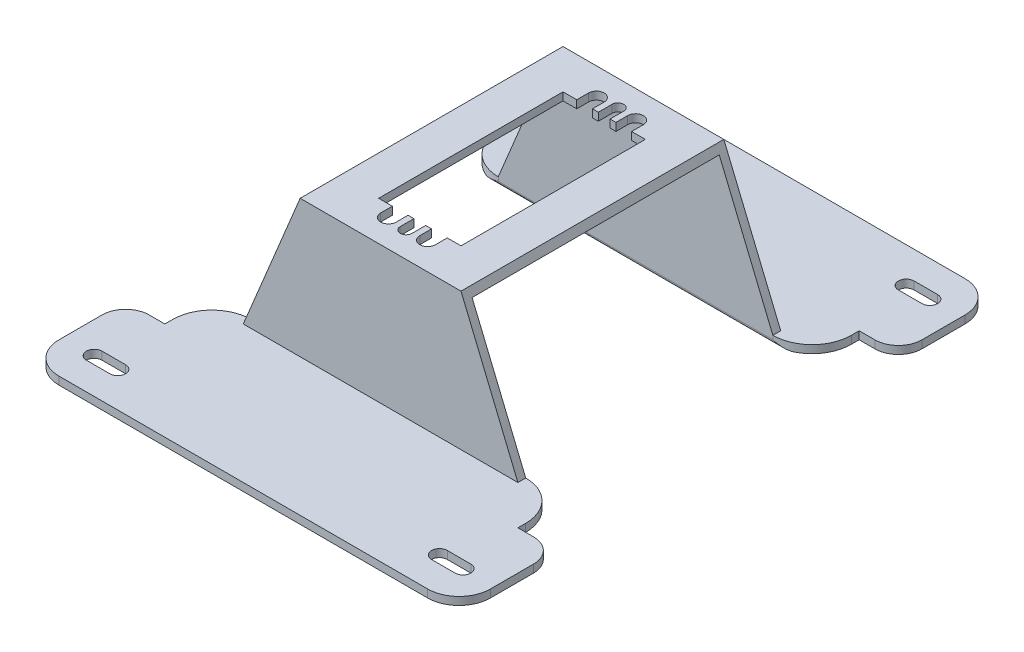
SolidWorks part; units mm, degrees
ref_plane "前视基准面" through (0, 0, 0) normal (0, 0, 1) x (1, 0, 0)
ref_plane "上视基准面" through (0, 0, 0) normal (0, 1, 0) x (1, 0, 0)
ref_plane "右视基准面" through (0, 0, 0) normal (1, 0, 0) x (0, 0, -1)
sketch "草图1" plane through (0, 0, 0) normal (0, 1, 0) x (1, 0, 0)
  line L0 (0, 29) -> (0, 18)
  line L1 (20, 0) -> (90, 0)
  line L2 (8, -93) -> (14, -93)
  line L3 (8, 37) -> (102, 37)
  line L4 (110, 18) -> (110, 29)
  line L5 (102, 30) -> (96, 30)
  line L6 (6, 12) -> (10, 12)
  line L7 (10, 12) -> (10, 10)
  line L8 (102, 26) -> (96, 26)
  line L9 (100, 12) -> (100, 10)
  line L10 (100, 12) -> (104, 12)
  line L12 (8, 26) -> (14, 26)
  line L13 (8, -89) -> (14, -89)
  line L14 (8, 30) -> (14, 30)
  line L15 (100, -75) -> (104, -75)
  line L16 (100, -75) -> (100, -73)
  line L17 (102, -89) -> (96, -89)
  line L18 (10, -75) -> (10, -73)
  line L19 (6, -75) -> (10, -75)
  line L20 (102, -93) -> (96, -93)
  line L21 (110, -81) -> (110, -92)
  line L22 (8, -100) -> (102, -100)
  line L23 (20, -63) -> (90, -63)
  line L24 (0, -92) -> (0, -81)
  arc A0 (8, 30) -> (8, 26) centre (8, 28) ccw
  arc A1 (14, 26) -> (14, 30) centre (14, 28) ccw
  arc A2 (96, 26) -> (96, 30) centre (96, 28) cw
  arc A3 (102, 30) -> (102, 26) centre (102, 28) cw
  arc A4 (8, 37) -> (0, 29) centre (8, 29) ccw
  arc A5 (110, 29) -> (102, 37) centre (102, 29) ccw
  arc A6 (20, 0) -> (10, 10) centre (20, 10) cw
  arc A7 (90, 0) -> (100, 10) centre (90, 10) ccw
  arc A8 (6, 12) -> (0, 18) centre (6, 18) cw
  arc A9 (110, 18) -> (104, 12) centre (104, 18) cw
  arc A10 (110, -81) -> (104, -75) centre (104, -81) ccw
  arc A11 (6, -75) -> (0, -81) centre (6, -81) ccw
  arc A12 (90, -63) -> (100, -73) centre (90, -73) cw
  arc A13 (20, -63) -> (10, -73) centre (20, -73) ccw
  arc A14 (110, -92) -> (102, -100) centre (102, -92) cw
  arc A15 (8, -100) -> (0, -92) centre (8, -92) cw
  arc A16 (102, -93) -> (102, -89) centre (102, -91) ccw
  arc A17 (96, -89) -> (96, -93) centre (96, -91) ccw
  arc A18 (14, -89) -> (14, -93) centre (14, -91) cw
  arc A19 (8, -93) -> (8, -89) centre (8, -91) cw
  dimension "D1" = 6
extrude "凸台-拉伸1" add sketch "草图1" along normal blind 2
ref_plane "基准面1" through (0, 0, 31.5) normal (0, 0, 1) x (1, 0, 0)
sketch "草图2" plane through (0, 0, 31.5) normal (0, 0, 1) x (1, 0, 0)
  line L0 (20, 2) -> (90, 2) construction
  line L1 (20, 2) -> (90, 2)
  line L3 (55, 37) -> (75.5, 37)
  line L4 (55, 37) -> (34.5, 37)
  line L5 (34.5, 37) -> (20, 2)
  line L6 (75.5, 37) -> (90, 2)
extrude "凸台-拉伸3" add sketch "草图2" along normal blind 33.5 and the other way blind 33.5
sketch "草图3" plane through (0, 0, 0) normal (1, 0, 0) x (0, 0, -1)
  line L6 (-63, 2) -> (-63, 1)
  line L9 (0, 2) -> (0, 35)
  line L10 (0, 35) -> (-63, 35)
  line L11 (-63, 2) -> (-63, 35)
  line L12 (-64, 0) -> (1, 0)
  line L13 (0, 2) -> (0, 1)
  arc A0 (-64, 0) -> (-63, 1) centre (-64, 1) ccw
  arc A1 (1, 0) -> (0, 1) centre (1, 1) cw
  point P4 (2, 37)
  point P5 (-65, 37)
  point P10 (2, 35)
  point P19 (-31.5, 35)
extrude "切除-拉伸3" cut sketch "草图3" against normal blind 33.5 and the other way through all
sketch "草图4" plane through (0, 0, 0) normal (0, 1, 0) x (1, 0, 0)
  line L0 (48, -8) -> (44.5, -8)
  line L5 (44.5, -8) -> (44.5, -55)
  line L10 (53.5, -58.5) -> (53.5, -55)
  line L11 (65.5, -8) -> (65.5, -55)
  line L12 (65.5, -8) -> (62, -8)
  line L13 (56.5, -4.5) -> (56.5, -8)
  line L14 (53.5, -8) -> (52, -8)
  line L15 (52, -55) -> (52, -58)
  line L16 (48, -58) -> (48, -55)
  line L17 (62, -5) -> (62, -8)
  line L18 (58, -55) -> (58, -58)
  line L19 (58, -8) -> (58, -5)
  line L20 (48, -5) -> (48, -8)
  line L21 (52, -8) -> (52, -5)
  line L22 (53.5, -4.5) -> (53.5, -8)
  line L24 (62, -58) -> (62, -55)
  line L25 (56.5, -58.5) -> (56.5, -55)
  line L26 (65.5, -55) -> (62, -55)
  line L28 (58, -8) -> (56.5, -8)
  line L29 (48, -55) -> (44.5, -55)
  line L30 (53.5, -55) -> (52, -55)
  line L31 (58, -55) -> (56.5, -55)
  arc A0 (52, -5) -> (48, -5) centre (50, -5) ccw
  arc A1 (56.5, -4.5) -> (53.5, -4.5) centre (55, -4.5) ccw
  arc A2 (62, -5) -> (58, -5) centre (60, -5) ccw
  arc A3 (62, -58) -> (58, -58) centre (60, -58) cw
  arc A4 (56.5, -58.5) -> (53.5, -58.5) centre (55, -58.5) cw
  arc A5 (52, -58) -> (48, -58) centre (50, -58) cw
extrude "切除-拉伸6" cut sketch "草图4" along direction (0, 1, 0) on the side of the normal through all
